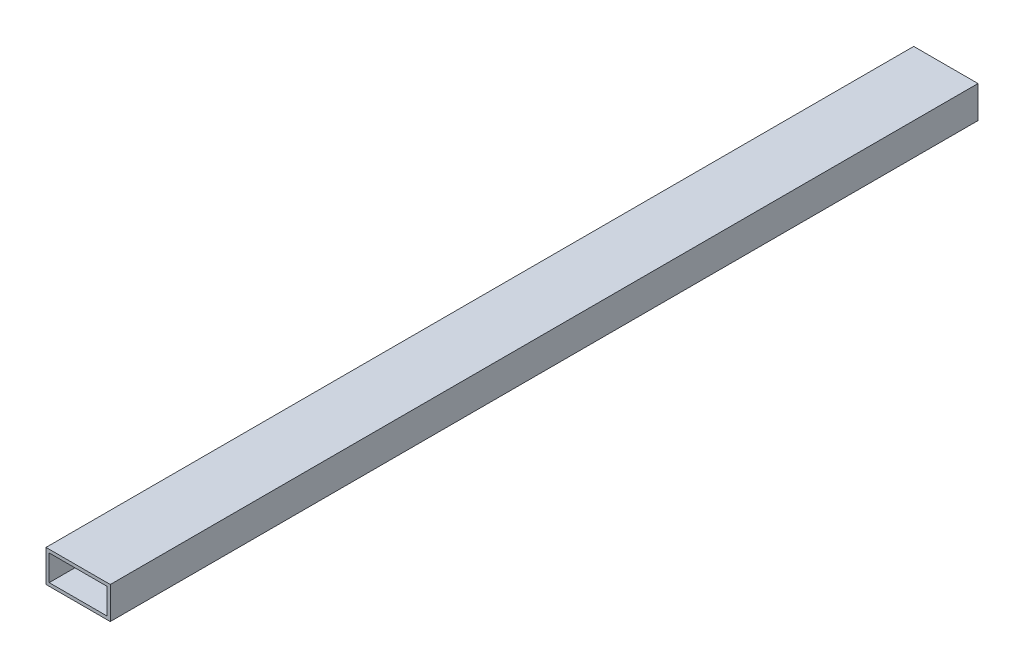
SolidWorks part; units mm, degrees
ref_plane "Front Plane" through (0, 0, 0) normal (0, 0, 1) x (1, 0, 0)
ref_plane "Top Plane" through (0, 0, 0) normal (0, 1, 0) x (1, 0, 0)
ref_plane "Right Plane" through (0, 0, 0) normal (1, 0, 0) x (0, 0, -1)
sketch "Sketch1" plane through (0, 0, 0) normal (0, 0, 1) x (1, 0, 0)
  line L0 (-9, 4) -> (9, 4)
  line L1 (-10, -5) -> (10, -5)
  line L2 (-10, -5) -> (-10, 5)
  line L3 (-10, 5) -> (10, 5)
  line L4 (10, -5) -> (10, 5)
  line L5 (-10, -5) -> (10, 5) construction
  line L6 (-10, 5) -> (10, -5) construction
  line L7 (9, -4) -> (9, 4)
  line L8 (-9, -4) -> (9, -4)
  line L9 (-9, -4) -> (-9, 4)
  point P0 (0, 0)
  dimension "D2" = 20
  dimension "D3" = 10
  dimension "D1" = 1
extrude "Boss-Extrude1" add sketch "Sketch1" along normal blind 270
